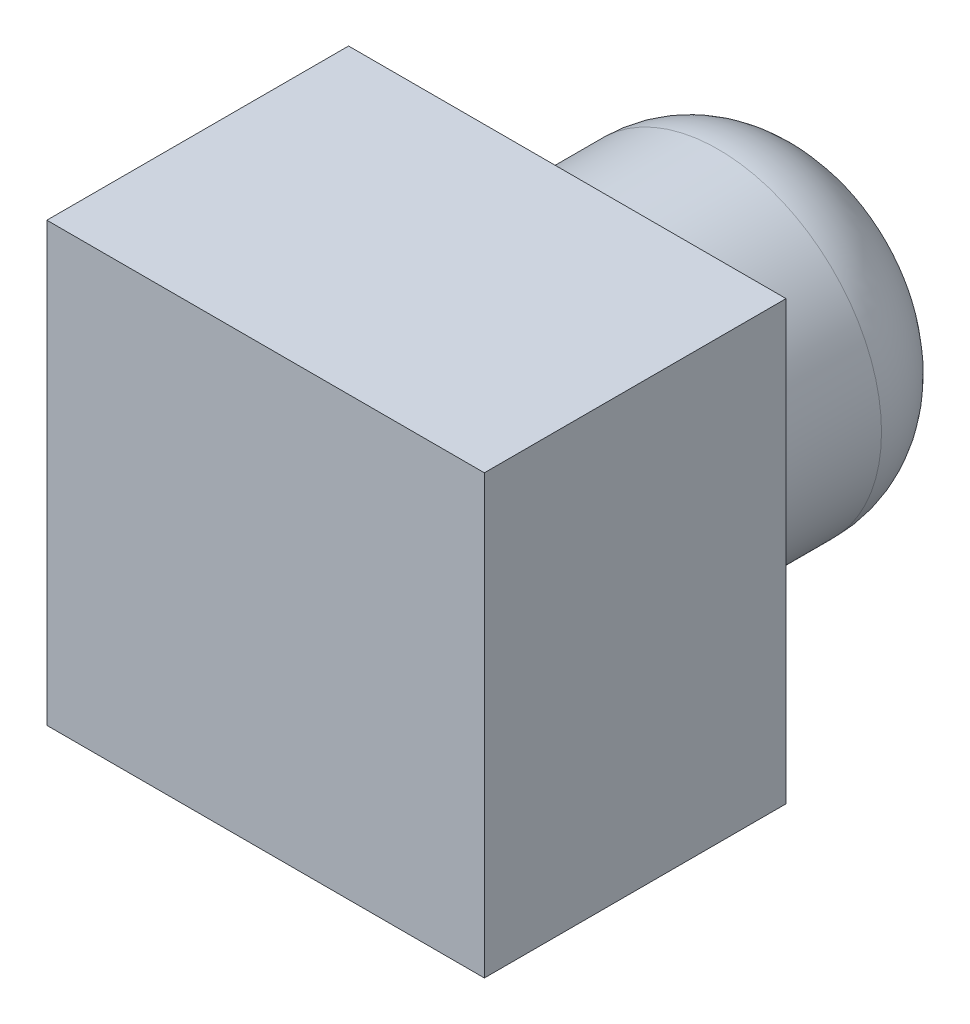
SolidWorks part; units mm, degrees
ref_plane "Front Plane" through (0, 0, 0) normal (0, 0, 1) x (1, 0, 0)
ref_plane "Top Plane" through (0, 0, 0) normal (0, 1, 0) x (1, 0, 0)
ref_plane "Right Plane" through (0, 0, 0) normal (1, 0, 0) x (0, 0, -1)
sketch "Sketch1" plane through (0, 0, 0) normal (0, 0, 1) x (1, 0, 0)
  line L1 (-1.105, 1.105) -> (1.105, 1.105)
  line L2 (-1.105, 1.105) -> (-1.105, -1.105)
  line L3 (-1.105, -1.105) -> (1.105, -1.105)
  line L4 (1.105, 1.105) -> (1.105, -1.105)
  line L5 (-1.105, 1.105) -> (1.105, -1.105) construction
  line L6 (-1.105, -1.105) -> (1.105, 1.105) construction
  point P0 (0, 0)
  dimension "D1" = 2.21
  dimension "D2" = 2.21
extrude "Boss-Extrude1" add sketch "Sketch1" along normal blind 1.524
sketch "Sketch2" plane through (0, 0, 0) normal (0, 0, -1) x (-1, 0, 0)
  circle A0 centre (0, 0) radius 0.825
  dimension "D1" = 1.65
extrude "Boss-Extrude2" add sketch "Sketch2" along normal blind 1.27
fillet "Fillet1" radius 0.508 1 edges at (-0.825, 0, -1.27)
